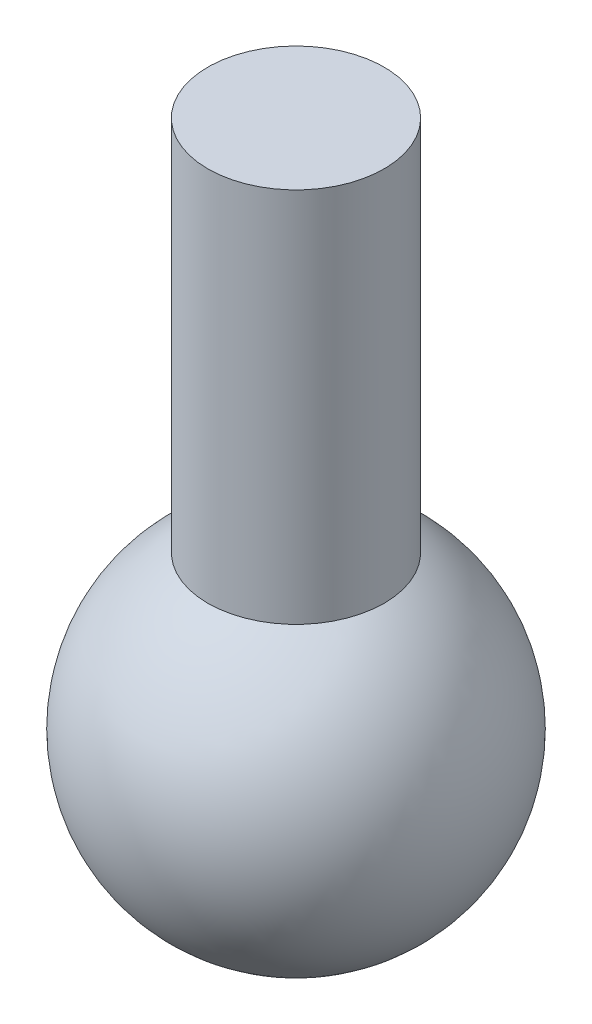
SolidWorks part; units mm, degrees
ref_plane "Front Plane" through (0, 0, 0) normal (0, 0, 1) x (1, 0, 0)
ref_plane "Top Plane" through (0, 0, 0) normal (0, 1, 0) x (1, 0, 0)
ref_plane "Right Plane" through (0, 0, 0) normal (1, 0, 0) x (0, 0, -1)
sketch "Sketch1" plane through (0, 0, 0) normal (0, 0, 1) x (1, 0, 0)
  line L0 (0, 0) -> (0, 12)
  line L1 (0, 12) -> (1.5, 12)
  line L2 (1.5, 12) -> (1.5, 5.5981)
  line L3 (0, 0) -> (0, -9.2634) construction
  arc A0 (0, 0) -> (1.5, 5.5981) centre (0, 3) ccw
  point P6 (1.8763, 9.7735)
  dimension "D1" = 6
  dimension "D2" = 3
  dimension "D3" = 12
revolve "Revolve1" add sketch "Sketch1" angle 360 about L3
